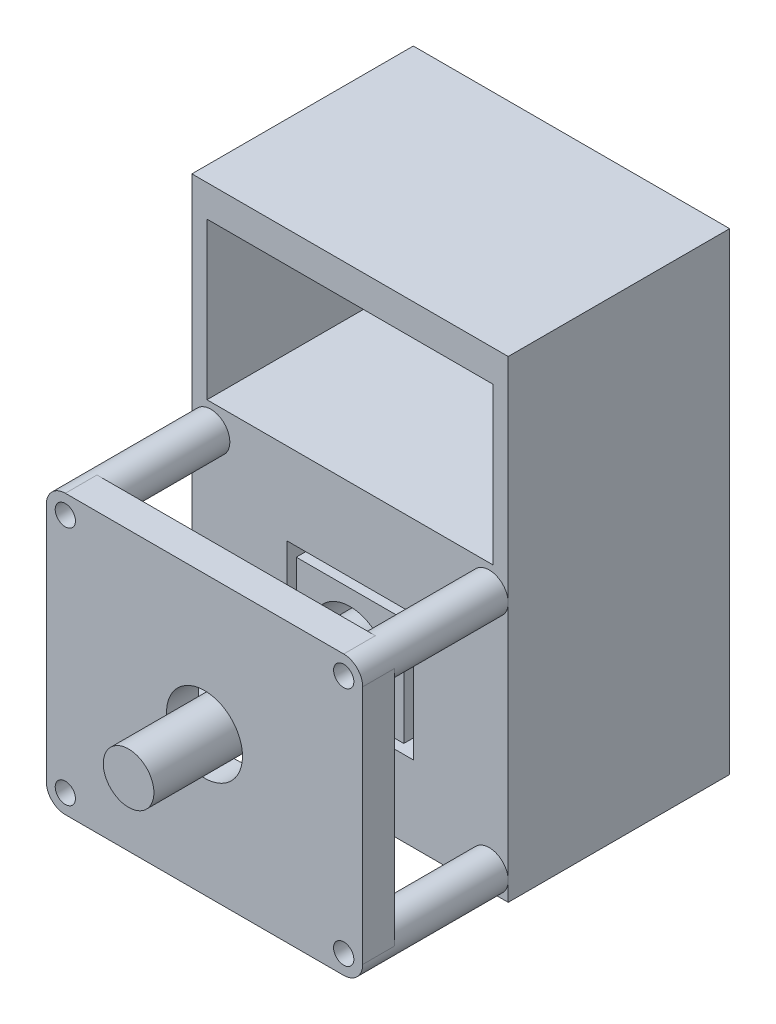
SolidWorks part; units mm, degrees
ref_plane "正面" through (0, 0, 0) normal (0, 0, 1) x (1, 0, 0)
ref_plane "平面" through (0, 0, 0) normal (0, 1, 0) x (1, 0, 0)
ref_plane "右側面" through (0, 0, 0) normal (1, 0, 0) x (0, 0, -1)
sketch "ｽｹｯﾁ2" plane through (0, 0, 0) normal (0, 0, 1) x (1, 0, 0)
  line L0 (-25, 22) -> (25, 22) construction
  line L1 (-10, 10) -> (10, 10)
  line L2 (-10, 10) -> (-10, -10)
  line L3 (-10, -10) -> (10, -10)
  line L4 (10, 10) -> (10, -10)
  line L5 (-10, 10) -> (10, -10) construction
  line L6 (-10, -10) -> (10, 10) construction
  line L11 (0, 47.7203) -> (0, 0) construction
  line L12 (-25, 52.7203) -> (-25, -22)
  line L13 (-25, -22) -> (25, -22)
  line L15 (25, 52.7203) -> (25, -22)
  line L16 (22.615, 22.9903) -> (-22.615, 22.9903)
  line L17 (-8.5, 8.5) -> (8.5, 8.5)
  line L18 (-8.5, 8.5) -> (-8.5, -8.5)
  line L19 (-8.5, -8.5) -> (8.5, -8.5)
  line L20 (8.5, 8.5) -> (8.5, -8.5)
  line L21 (-8.5, 8.5) -> (8.5, -8.5) construction
  line L22 (-8.5, -8.5) -> (8.5, 8.5) construction
  line L23 (22.615, 22.9903) -> (22.615, 47.7203)
  line L24 (22.615, 47.7203) -> (-22.615, 47.7203)
  line L25 (-22.615, 22.9903) -> (-22.615, 47.7203)
  line L26 (12.5, 22.9903) -> (12.5, 47.7203) construction
  line L27 (-25, 52.7203) -> (25, 52.7203)
  circle A0 centre (0, 0) radius 25 construction
  circle A2 centre (0, 0) radius 6
  circle A3 centre (-22, 19) radius 3 construction
  circle A4 centre (22, 19) radius 3 construction
  circle A5 centre (22, -19) radius 3 construction
  circle A6 centre (-22, -19) radius 3 construction
  circle A7 centre (-22, 19) radius 1.6
  circle A8 centre (-22, -19) radius 1.6
  circle A9 centre (22, -19) radius 1.6
  circle A10 centre (22, 19) radius 1.6
  circle A11 centre (12.5, 35.3553) radius 12.5 construction
  point P0 (0, 0)
  dimension "D2" = 50
  dimension "D3" = 50
  dimension "D12" = 12
  dimension "D13" = 6
  dimension "D14" = 3.2
  dimension "D10" = 25
  dimension "D1" = 20
  dimension "D4" = 22
  dimension "D5" = 25
  dimension "D6" = 22
  dimension "D7" = 45.23
  dimension "D8" = 24.73
  dimension "D9" = 12.5
  dimension "D11" = 17
  dimension "D15" = 5
extrude "ﾎﾞｽ - 押し出し1" add sketch "ｽｹｯﾁ2" against normal blind 35
sketch "ｽｹｯﾁ3" plane through (0, 0, 0) normal (0, 0, 1) x (1, 0, 0)
  circle A0 centre (0, 0) radius 4
  point P3 (0, 0)
  dimension "D1" = 8
extrude "ﾎﾞｽ - 押し出し2" add sketch "ｽｹｯﾁ3" against normal blind 37 and the other way blind 35 separate body
sketch "ｽｹｯﾁ6" plane through (0, 0, 0) normal (0, 0, 1) x (1, 0, 0)
  line L0 (-27.385, 0) -> (10, 0) construction
  line L3 (0, 10) -> (0, -10) construction
  line L4 (-10, 10) -> (10, 10) construction
  line L5 (-10, -10) -> (10, -10) construction
  line L6 (10, 10) -> (10, -10) construction
  circle A0 centre (-22, 19) radius 3
  circle A1 centre (-22, 19) radius 1.6
  circle A2 centre (-22, 19) radius 1.6 construction
  circle A3 centre (-22, -19) radius 1.6
  circle A4 centre (-22, -19) radius 3
  circle A5 centre (22, -19) radius 3
  circle A6 centre (22, -19) radius 1.6
  circle A7 centre (22, 19) radius 1.6
  circle A8 centre (22, 19) radius 3
  point P6 (10, 0)
  point P8 (0, 0)
  dimension "D1" = 6
extrude "ﾎﾞｽ - 押し出し3" add sketch "ｽｹｯﾁ6" along normal blind 18 separate body
sketch "ｽｹｯﾁ7" plane through (0, 0, 18) normal (0, 0, 1) x (1, 0, 0)
  line L0 (-22, 22) -> (22, 22)
  line L1 (-25, 19) -> (-25, -19)
  line L2 (-22, -22) -> (22, -22)
  line L3 (25, 19) -> (25, -19)
  circle A0 centre (-22, -19) radius 3 construction
  circle A1 centre (22, -19) radius 3 construction
  circle A2 centre (22, 19) radius 3 construction
  circle A3 centre (-22, 19) radius 3 construction
  arc A4 (-25, -19) -> (-22, -22) centre (-22, -19) ccw
  arc A5 (22, -22) -> (25, -19) centre (22, -19) ccw
  arc A6 (25, 19) -> (22, 22) centre (22, 19) ccw
  arc A7 (-22, 22) -> (-25, 19) centre (-22, 19) ccw
  circle A8 centre (-22, -19) radius 1.6 construction
  circle A9 centre (22, -19) radius 1.6 construction
  circle A10 centre (22, 19) radius 1.6 construction
  circle A11 centre (-22, 19) radius 1.6 construction
  circle A12 centre (-22, -19) radius 1.6
  circle A13 centre (22, -19) radius 1.6
  circle A14 centre (22, 19) radius 1.6
  circle A15 centre (-22, 19) radius 1.6
  circle A16 centre (0, 0) radius 6
  circle A17 centre (0, 0) radius 4 construction
  dimension "D1" = 12
extrude "ﾎﾞｽ - 押し出し4" add sketch "ｽｹｯﾁ7" along normal blind 5
